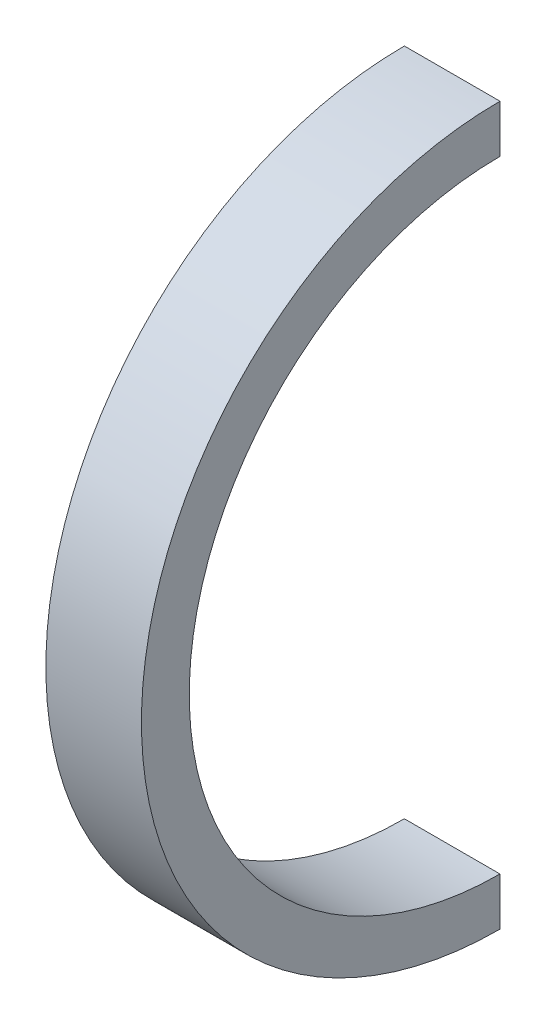
SolidWorks part; units mm, degrees
ref_plane "Front Plane" through (0, 0, 0) normal (0, 0, 1) x (1, 0, 0)
ref_plane "Top Plane" through (0, 0, 0) normal (0, 1, 0) x (1, 0, 0)
ref_plane "Right Plane" through (0, 0, 0) normal (1, 0, 0) x (0, 0, -1)
sketch "Sketch1" plane through (0, 0, 0) normal (1, 0, 0) x (0, 0, -1)
  circle A0 centre (0, 0) radius 82.55
  circle A1 centre (0, 0) radius 95.25
  dimension "D1" = 165.1
  dimension "D2" = 190.5
extrude "Boss-Extrude1" add sketch "Sketch1" along normal blind 25.4
sketch "Sketch2" plane through (0, 0, 0) normal (-1, 0, 0) x (0, 0, 1)
  line L1 (0, 95.25) -> (-95.25, 95.25)
  line L2 (0, 95.25) -> (0, -95.25)
  line L3 (0, -95.25) -> (-95.25, -95.25)
  line L4 (-95.25, 95.25) -> (-95.25, -95.25)
  circle A0 centre (0, 0) radius 95.25 construction
extrude "Cut-Extrude1" cut sketch "Sketch2" against normal blind 25.4
